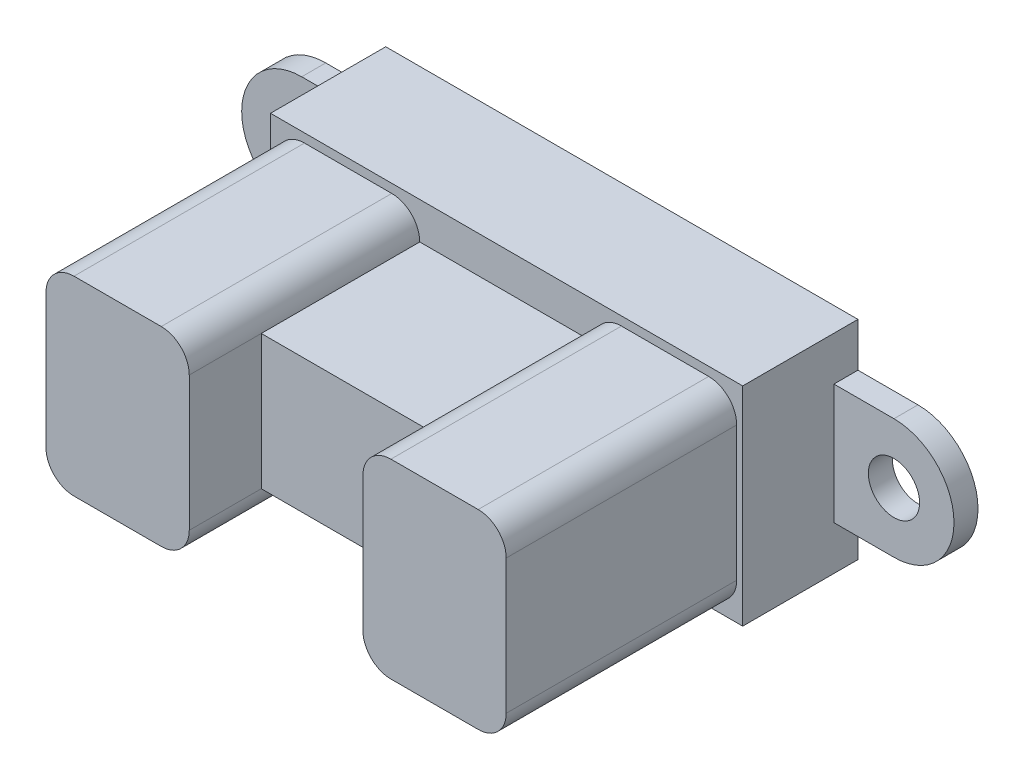
SolidWorks part; units mm, degrees
ref_plane "정면" through (0, 0, 0) normal (0, 0, 1) x (1, 0, 0)
ref_plane "윗면" through (0, 0, 0) normal (0, 1, 0) x (1, 0, 0)
ref_plane "우측면" through (0, 0, 0) normal (1, 0, 0) x (0, 0, -1)
sketch "스케치1" plane through (0, 0, 0) normal (0, 0, 1) x (1, 0, 0)
  line L0 (-31.8886, 0) -> (35.6085, 0) construction
  line L1 (0, -26.5586) -> (0, 40.058) construction
  line L3 (-14.75, 6.5) -> (14.75, 6.5)
  line L4 (-14.75, 6.5) -> (-14.75, -6.5)
  line L5 (-14.75, -6.5) -> (14.75, -6.5)
  line L6 (14.75, 6.5) -> (14.75, -6.5)
  line L7 (-14.75, 6.5) -> (14.75, -6.5) construction
  line L8 (-14.75, -6.5) -> (14.75, 6.5) construction
  point P4 (0, 0)
  dimension "D1" = 29.5
  dimension "D2" = 13
extrude "보스-돌출1" add sketch "스케치1" along normal blind 7.2
sketch "스케치3" plane through (0, 0, 0) normal (0, 0, 1) x (1, 0, 0)
  line L0 (-2.8866, 0) -> (3.4364, 0) construction
  line L1 (0, 1.9106) -> (0, -3.0378) construction
  line L3 (-14.75, 6.5) -> (-14.75, -6.5) construction
  line L4 (-18.5, 3.75) -> (-14.75, 3.75)
  line L5 (-18.5, -3.75) -> (-14.75, -3.75)
  line L6 (-14.75, -3.75) -> (-14.75, 3.75)
  line L7 (14.75, -3.75) -> (14.75, 3.75)
  line L8 (18.5, -3.75) -> (14.75, -3.75)
  line L9 (18.5, 3.75) -> (14.75, 3.75)
  arc A0 (-18.5, 3.75) -> (-18.5, -3.75) centre (-18.5, 0) ccw
  circle A1 centre (-18.5, 0) radius 1.6
  circle A2 centre (18.5, 0) radius 1.6
  arc A3 (18.5, 3.75) -> (18.5, -3.75) centre (18.5, 0) cw
  dimension "D1" = 7.5
  dimension "D2" = 3.2
  dimension "D3" = 37
extrude "보스-돌출2" add sketch "스케치3" along normal blind 1.5
sketch "스케치4" plane through (0, 0, 7.2) normal (0, 0, 1) x (1, 0, 0)
  line L0 (0, 3.8774) -> (0, -5.2045) construction
  line L1 (3.5249, 0) -> (-5.8058, 0) construction
  line L3 (-7.175, -5.95) -> (-12.625, -5.95)
  line L4 (-5.425, -4.2) -> (-5.425, 4.2)
  line L5 (-7.175, 5.95) -> (-12.625, 5.95)
  line L6 (-14.375, -4.2) -> (-14.375, 4.2)
  line L7 (-5.425, -5.95) -> (-14.375, 5.95) construction
  line L8 (-5.425, 5.95) -> (-14.375, -5.95) construction
  line L9 (5.425, 5.95) -> (14.375, -5.95) construction
  line L10 (5.425, -5.95) -> (14.375, 5.95) construction
  line L11 (14.375, -4.2) -> (14.375, 4.2)
  line L12 (7.175, 5.95) -> (12.625, 5.95)
  line L13 (5.425, -4.2) -> (5.425, 4.2)
  line L14 (7.175, -5.95) -> (12.625, -5.95)
  arc A0 (-7.175, -5.95) -> (-5.425, -4.2) centre (-7.175, -4.2) ccw
  arc A1 (-12.625, -5.95) -> (-14.375, -4.2) centre (-12.625, -4.2) cw
  arc A2 (-12.625, 5.95) -> (-14.375, 4.2) centre (-12.625, 4.2) ccw
  arc A3 (-5.425, 4.2) -> (-7.175, 5.95) centre (-7.175, 4.2) ccw
  arc A4 (5.425, 4.2) -> (7.175, 5.95) centre (7.175, 4.2) cw
  arc A5 (12.625, 5.95) -> (14.375, 4.2) centre (12.625, 4.2) cw
  arc A6 (12.625, -5.95) -> (14.375, -4.2) centre (12.625, -4.2) ccw
  arc A7 (7.175, -5.95) -> (5.425, -4.2) centre (7.175, -4.2) cw
  point P4 (-9.9, 0)
  point P38 (9.9, 0)
  dimension "D4" = 1.75
  dimension "D1" = 8.95
  dimension "D2" = 11.9
  dimension "D3" = 19.8
extrude "보스-돌출3" add sketch "스케치4" along normal blind 14.4
sketch "스케치5" plane through (0, 0, 7.2) normal (0, 0, 1) x (1, 0, 0)
  line L0 (5.425, 4.2) -> (5.425, -4.2) construction
  line L1 (-5.425, -4.2) -> (5.425, -4.2)
  line L2 (-5.425, -4.2) -> (-5.425, 4.2)
  line L3 (-5.425, 4.2) -> (5.425, 4.2)
  line L4 (5.425, -4.2) -> (5.425, 4.2)
  line L5 (-5.425, -4.2) -> (5.425, 4.2) construction
  line L6 (-5.425, 4.2) -> (5.425, -4.2) construction
  point P0 (0, 0)
  dimension "D1" = 8.4
extrude "보스-돌출4" add sketch "스케치5" along normal blind 9.9
